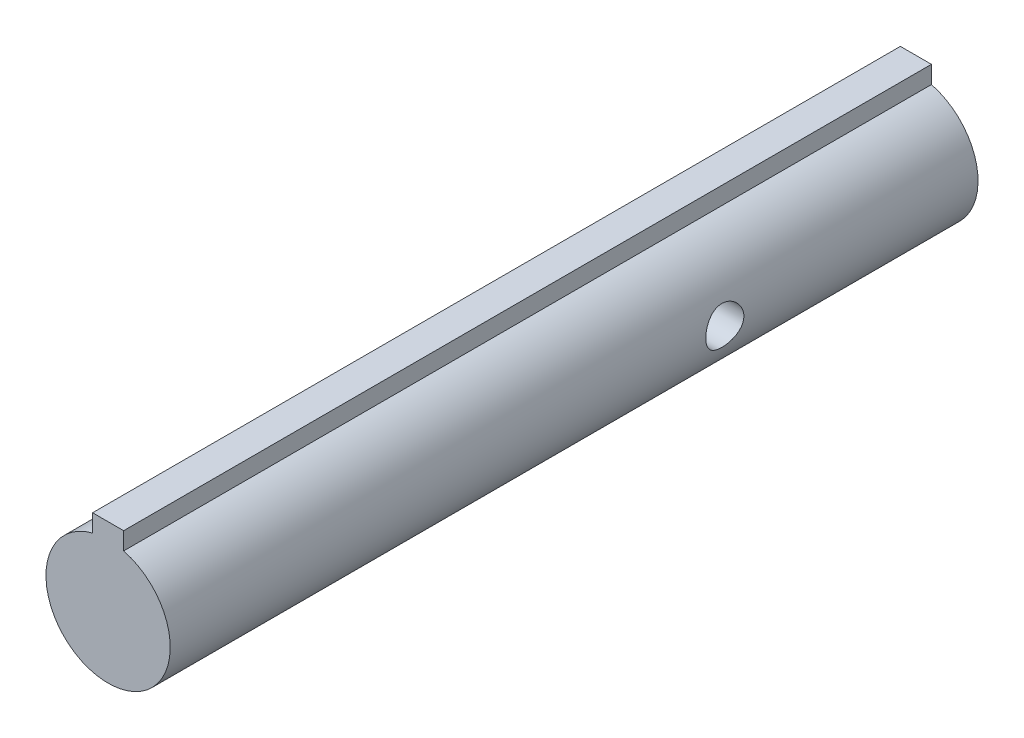
SolidWorks part; units mm, degrees
material "AISI 316 Annealed Stainless Steel Bar (SS)"
ref_plane "Front Plane" through (0, 0, 0) normal (0, 0, 1) x (1, 0, 0)
ref_plane "Top Plane" through (0, 0, 0) normal (0, 1, 0) x (1, 0, 0)
ref_plane "Right Plane" through (0, 0, 0) normal (1, 0, 0) x (0, 0, -1)
sketch "Sketch1" plane through (0, 0, 0) normal (0, 0, 1) x (1, 0, 0)
  line L0 (-1, 3.873) -> (-1, 5.003)
  line L1 (-1, 5.003) -> (1, 5.003)
  line L2 (1, 5.003) -> (1, 3.873)
  arc A0 (-1, 3.873) -> (1, 3.873) centre (0, 0) ccw
  dimension "D1" = 8
  dimension "D2" = 1
  dimension "D3" = 2
  dimension "D4" = 1.13
extrude "Boss-Extrude1" add sketch "Sketch1" along normal blind 52
sketch "Sketch2" plane through (0, 0, 0) normal (1, 0, 0) x (0, 0, -1)
  line L0 (0, -4) -> (0, 3.873) construction
  circle A0 centre (-16.3, 0) radius 1.225
  dimension "D2" = 2.45
  dimension "D1" = 16.3
extrude "Cut-Extrude1" cut sketch "Sketch2" against normal mid plane 50
